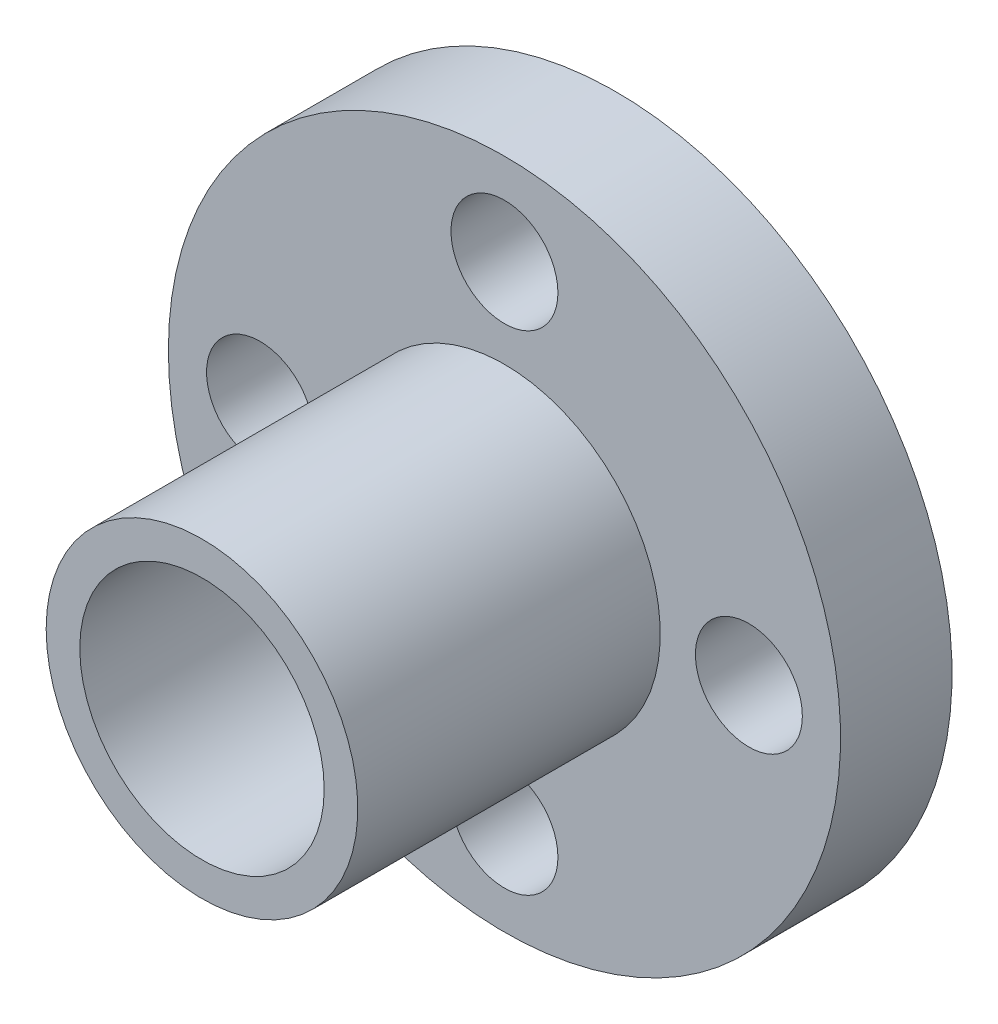
SolidWorks part; units mm, degrees
ref_plane "Front Plane" through (0, 0, 0) normal (0, 0, 1) x (1, 0, 0)
ref_plane "Top Plane" through (0, 0, 0) normal (0, 1, 0) x (1, 0, 0)
ref_plane "Right Plane" through (0, 0, 0) normal (1, 0, 0) x (0, 0, -1)
sketch "Sketch1" plane through (0, 0, 0) normal (0, 1, 0) x (1, 0, 0)
  line L1 (11, -1.5) -> (11, -5.15)
  line L2 (11, -5.15) -> (5.1, -5.15)
  line L3 (5.1, -5.15) -> (5.1, -15.05)
  line L4 (5.1, -15.05) -> (4, -15.05)
  line L5 (4, -15.05) -> (4, 0)
  line L6 (0, 0) -> (0, -36.5462) construction
  line L7 (11, -1.5) -> (5.1, -1.5)
  line L8 (5.1, -1.5) -> (5.1, 0)
  line L9 (5.1, 0) -> (4, 0)
  point P2 (0, 0)
  point P9 (4, -7.525)
  dimension "D1" = 22
  dimension "D2" = 8
  dimension "D3" = 10.2
  dimension "D4" = 3.65
  dimension "D5" = 15.05
  dimension "D6" = 1.5
revolve "Revolve1" add sketch "Sketch1" angle 360 about L6
hole_wizard "Ø3.5 (3.5) Diameter Hole1" positions "Sketch2" profile "Sketch3" hole size "Ø3.5" standard "ANSI Metric" end condition through all
sketch "Sketch2" plane through (0, 0, 5.15) normal (0, 0, 1) x (1, 0, 0)
  circle A0 centre (0, 0) radius 8 construction
  point P4 (0, 8)
  point P6 (8, 0)
  point P8 (0, -8)
  point P10 (-8, 0)
  dimension "D1" = 16
sketch "Sketch3" plane through (-8, 0, 5.15) normal (1, 0, 0) x (0, -1, 0)
  line L0 (0, 0) -> (0, 5.15)
  line L1 (0, 5.15) -> (1.75, 5.15)
  line L2 (1.75, 5.15) -> (1.75, 0)
  line L5 (1.75, 0) -> (0, 0)
  line L11 (0, -6.35) -> (0, 107.95) construction
  dimension "Thru Hole Dia." = 3.5
  dimension "Thru Hole Depth" = 5.15
